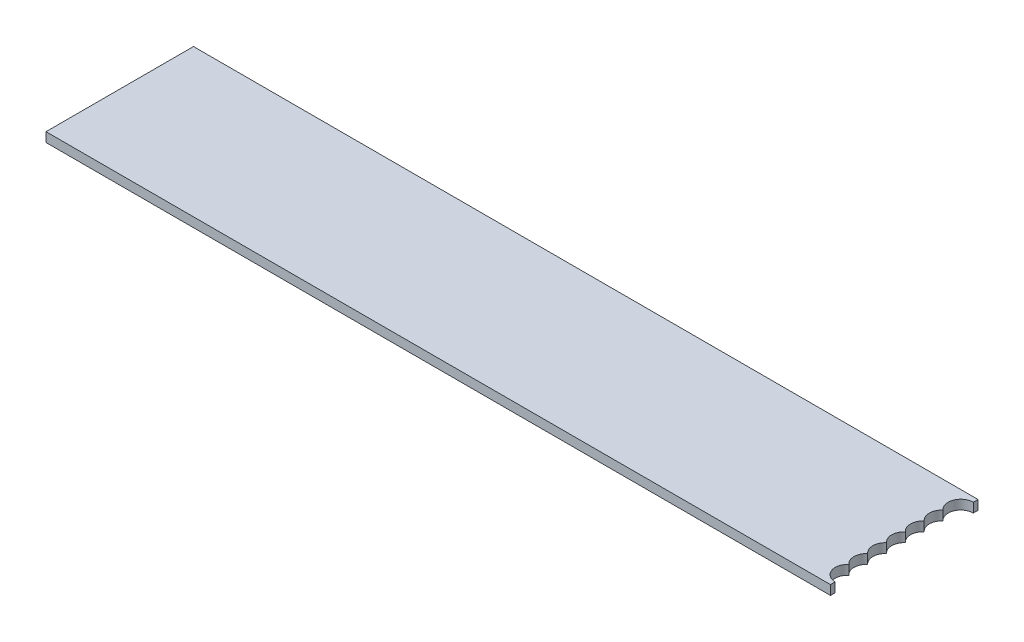
SolidWorks part; units mm, degrees
ref_plane "Спереди" through (0, 0, 0) normal (0, 0, 1) x (1, 0, 0)
ref_plane "Сверху" through (0, 0, 0) normal (0, 1, 0) x (1, 0, 0)
ref_plane "Справа" through (0, 0, 0) normal (1, 0, 0) x (0, 0, -1)
sketch "Эскиз1" plane through (0, 0, 0) normal (0, 1, 0) x (1, 0, 0)
  line L1 (-62.5, -11.75) -> (62.5, -11.75)
  line L2 (-62.5, -11.75) -> (-62.5, 11.75)
  line L3 (-62.5, 11.75) -> (62.5, 11.75)
  line L4 (62.5, -11.75) -> (62.5, 11.75)
  line L5 (-62.5, -11.75) -> (62.5, 11.75) construction
  line L6 (-62.5, 11.75) -> (62.5, -11.75) construction
  point P0 (0, 0)
extrude "Бобышка-Вытянуть1" add sketch "Эскиз1" along normal blind 1.5
sketch "Эскиз2" plane through (0, 1.5, 0) normal (0, 1, 0) x (1, 0, 0)
  line L0 (62.5, -11.75) -> (62.5, 11.75) construction
  circle A0 centre (62.5, 0) radius 2
  circle A1 centre (62.5, 3) radius 2
  circle A2 centre (62.5, 6) radius 2
  circle A3 centre (62.5, 9) radius 2
  circle A4 centre (62.5, 0) radius 2
  circle A5 centre (62.5, 3) radius 2
  circle A6 centre (62.5, 6) radius 2
  circle A7 centre (62.5, -3) radius 2
  circle A8 centre (62.5, 0) radius 2
  circle A9 centre (62.5, 3) radius 2
  circle A10 centre (62.5, -6) radius 2
  circle A11 centre (62.5, -3) radius 2
  circle A12 centre (62.5, 0) radius 2
  circle A13 centre (62.5, -3) radius 2
  circle A14 centre (62.5, -6) radius 2
  circle A15 centre (62.5, -9) radius 2
  line M1 (62.5, -11.75) -> (62.5, 11.75)
  dimension "D1" = 4
  dimension "D2" = 4
extrude "Вырез-Вытянуть1" cut sketch "Эскиз2" against normal through all contours A3 A2 M1 | A2 A3 M1 | A3 A2 A1 M1 | A1 A2 M1 | A2 A1 A0 M1 | A0 A1 M1 | A7 A1 A0 M1 | A7 A4 M1 | A10 A4 A7 M1 | A10 A7 M1 | A15 A7 A10 M1 | A15 A14 M1 | A14 A15 M1
